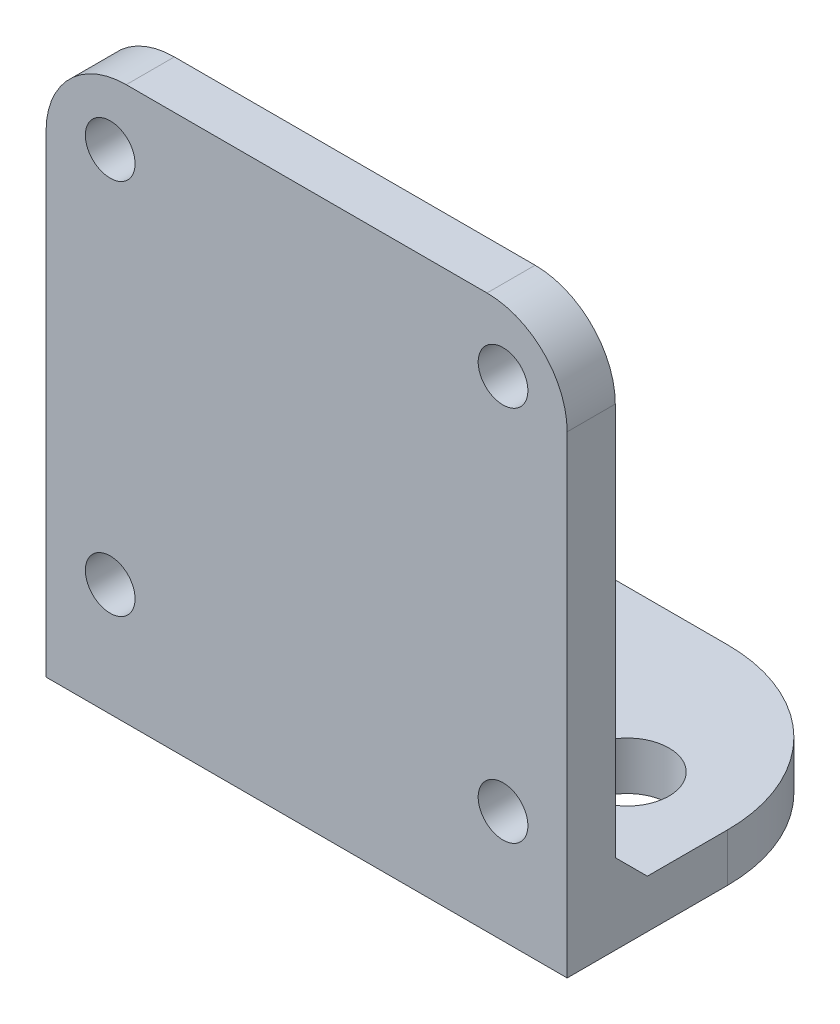
SolidWorks part; units mm, degrees
ref_plane "前视基准面" through (0, 0, 0) normal (0, 0, 1) x (1, 0, 0)
ref_plane "上视基准面" through (0, 0, 0) normal (0, 1, 0) x (1, 0, 0)
ref_plane "右视基准面" through (0, 0, 0) normal (1, 0, 0) x (0, 0, -1)
sketch "草图1" plane through (0, 0, 0) normal (0, 0, 1) x (1, 0, 0)
  line L3 (28.5, -27.5) -> (28.5, -30.5)
  line L4 (28.5, -30.5) -> (-4, -30.5)
  line L5 (-4, -30.5) -> (-4, -27.5)
  line L6 (28.5, -27.5) -> (28.5, 4)
  line L7 (-4, 4) -> (28.5, 4)
  line L8 (-4, 4) -> (-4, -27.5)
  circle A0 centre (0, 0) radius 1.55
  circle A1 centre (24.5, 0) radius 1.55
  circle A2 centre (0, -23.5) radius 1.55
  circle A3 centre (24.5, -23.5) radius 1.55
extrude "凸台-拉伸1" add sketch "草图1" along normal blind 3
sketch "草图2" plane through (0, 0, 0) normal (0, 0, -1) x (-1, 0, 0)
  line L0 (-28.5, -30.5) -> (4, -30.5)
  line L1 (4, -30.5) -> (4, -27.5)
  line L2 (4, 4) -> (4, -30.5) construction
  line L3 (-28.5, -30.5) -> (-28.5, -27.5)
  line L4 (-28.5, -30.5) -> (-28.5, 4) construction
  line L5 (-28.5, -27.5) -> (4, -27.5)
extrude "凸台-拉伸2" add sketch "草图2" along normal blind 17
sketch "草图3" plane through (0, -30.5, 0) normal (0, -1, 0) x (1, 0, 0)
  circle A0 centre (22.25, -7) radius 2.6
  circle A1 centre (2.25, -7) radius 2.6
extrude "切除-拉伸1" cut sketch "草图3" against normal blind 17
chamfer "倒角1" distance 2 angle 45 1 edges at (12.25, -27.5, 0)
fillet "圆角1" radius 10 2 edges at (-4, -29, -17) (28.5, -29, -17)
fillet "圆角2" radius 5 2 edges at (28.5, 4, 1.5) (-4, 4, 1.5)
